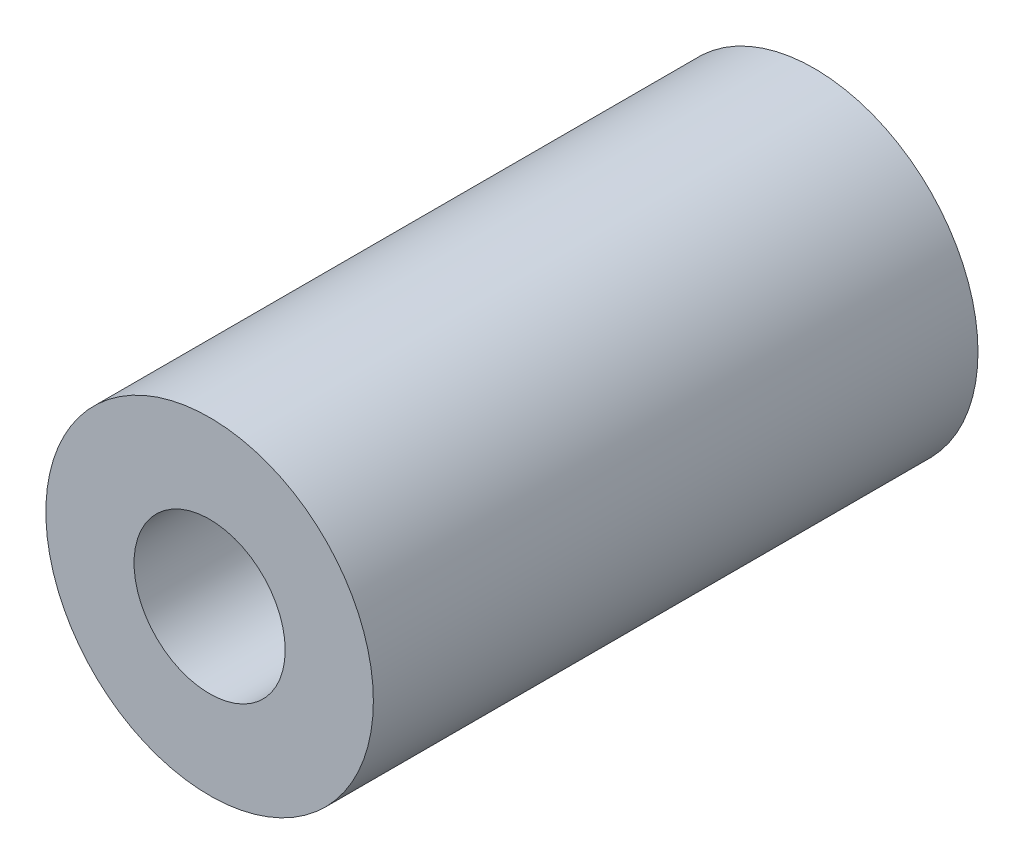
SolidWorks part; units mm, degrees
material "ABS"
ref_plane "前视基准面" through (0, 0, 0) normal (0, 0, 1) x (1, 0, 0)
ref_plane "上视基准面" through (0, 0, 0) normal (0, 1, 0) x (1, 0, 0)
ref_plane "右视基准面" through (0, 0, 0) normal (1, 0, 0) x (0, 0, -1)
sketch "草图1" plane through (0, 0, 0) normal (0, 0, 1) x (1, 0, 0)
  circle A0 centre (0, 0) radius 1.5
  circle A1 centre (0, 0) radius 3.25
  dimension "D1" = 3
  dimension "D2" = 6.5
extrude "凸台-拉伸1" add sketch "草图1" along normal blind 12
